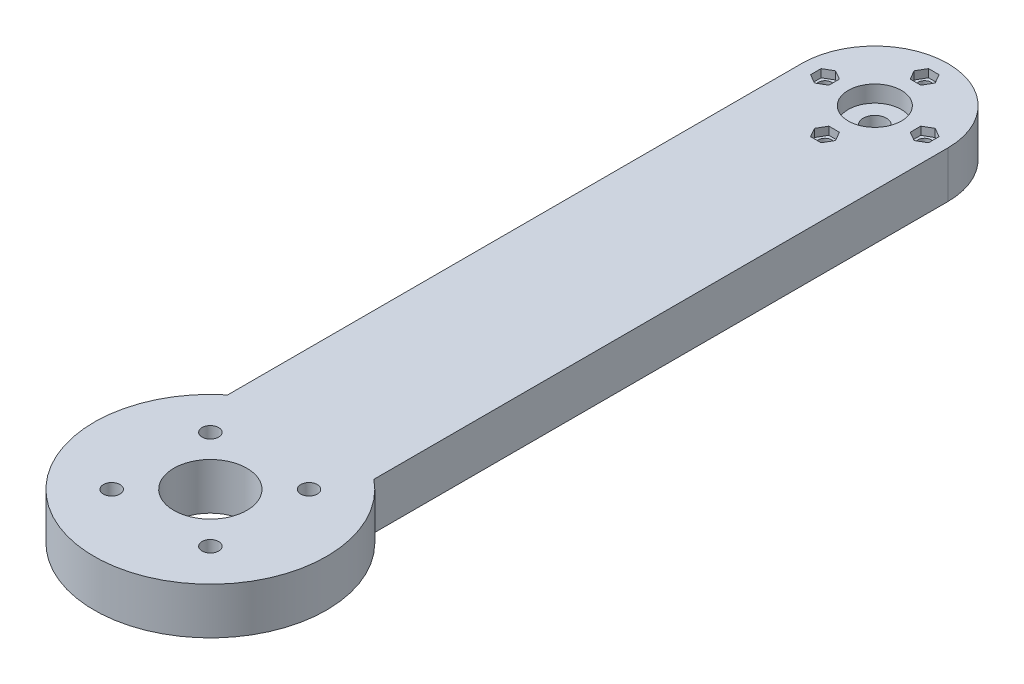
SolidWorks part; units mm, degrees
ref_plane "Front Plane" through (0, 0, 0) normal (0, 0, 1) x (1, 0, 0)
ref_plane "Top Plane" through (0, 0, 0) normal (0, 1, 0) x (1, 0, 0)
ref_plane "Right Plane" through (0, 0, 0) normal (1, 0, 0) x (0, 0, -1)
sketch "Sketch1" plane through (0, 0, 0) normal (0, 1, 0) x (1, 0, 0)
  line L0 (0, 0) -> (-42829.6201, 0) construction
  line L1 (0, 0) -> (0, -42829.6201) construction
  line L2 (-22, 0) -> (-22, -200)
  line L3 (22, 0) -> (22, -200)
  arc A0 (22, 0) -> (-22, 0) centre (0, 0) ccw
  arc A1 (-22, -200) -> (22, -200) centre (0, -200) ccw
  dimension "D1" = 44
  dimension "D2" = 44
  dimension "D3" = 200
extrude "Boss-Extrude1" add sketch "Sketch1" along normal blind 14
sketch "Sketch2" plane through (0, 14, 0) normal (0, 1, 0) x (1, 0, 0)
  line L0 (0, 0) -> (-50000, 0) construction
  line L1 (0, 0) -> (0, -50000) construction
  circle A0 centre (0, 0) radius 8
  dimension "D1" = 16
extrude "Cut-Extrude1" cut sketch "Sketch2" against normal blind 5
sketch "Sketch3" plane through (0, 14, 0) normal (0, 1, 0) x (1, 0, 0)
  line L0 (0, 0) -> (-50000, 0) construction
  line L1 (0, 0) -> (0, -50000) construction
  circle A0 centre (0, 0) radius 3.5
  dimension "D1" = 7
extrude "Cut-Extrude2" cut sketch "Sketch3" against normal through all
sketch "Sketch4" plane through (0, 14, 0) normal (0, 1, 0) x (1, 0, 0)
  line L0 (0, 0) -> (-50000, 0) construction
  line L1 (0, 0) -> (0, -50000) construction
  line L2 (15, -3.1754) -> (17.75, -1.5877)
  line L3 (3.1754, 15) -> (1.5877, 17.75)
  line L4 (1.5877, 17.75) -> (-1.5877, 17.75)
  line L5 (-1.5877, 17.75) -> (-3.1754, 15)
  line L6 (-3.1754, 15) -> (-1.5877, 12.25)
  line L7 (-1.5877, 12.25) -> (1.5877, 12.25)
  line L8 (1.5877, 12.25) -> (3.1754, 15)
  line L9 (17.75, -1.5877) -> (17.75, 1.5877)
  line L10 (17.75, 1.5877) -> (15, 3.1754)
  line L11 (15, 3.1754) -> (12.25, 1.5877)
  line L12 (12.25, 1.5877) -> (12.25, -1.5877)
  line L13 (12.25, -1.5877) -> (15, -3.1754)
  line L14 (-3.1754, -15) -> (-1.5877, -17.75)
  line L15 (-1.5877, -17.75) -> (1.5877, -17.75)
  line L16 (1.5877, -17.75) -> (3.1754, -15)
  line L17 (3.1754, -15) -> (1.5877, -12.25)
  line L18 (1.5877, -12.25) -> (-1.5877, -12.25)
  line L19 (-1.5877, -12.25) -> (-3.1754, -15)
  line L20 (-15, 3.1754) -> (-17.75, 1.5877)
  line L21 (-17.75, 1.5877) -> (-17.75, -1.5877)
  line L22 (-17.75, -1.5877) -> (-15, -3.1754)
  line L23 (-15, -3.1754) -> (-12.25, -1.5877)
  line L24 (-12.25, -1.5877) -> (-12.25, 1.5877)
  line L25 (-12.25, 1.5877) -> (-15, 3.1754)
  circle A1 centre (0, 0) radius 15 construction
  circle A6 centre (0, 15) radius 2.75 construction
  point P19 (0, 0)
  point P38 (0, 0)
  dimension "D1" = 30
  dimension "D2" = 5.5
  dimension "D3" = 4
extrude "Cut-Extrude9" cut sketch "Sketch4" against normal blind 2.4
sketch "Sketch7" plane through (0, 14, 0) normal (0, 1, 0) x (1, 0, 0)
  line L0 (0, 0) -> (-39424.2607, 0) construction
  line L1 (0, 0) -> (0, -50000) construction
  circle A2 centre (0, 0) radius 15 construction
  circle A3 centre (0, 15) radius 2
  circle A4 centre (15, 0) radius 2
  circle A5 centre (0, -15) radius 2
  circle A6 centre (-15, 0) radius 2
  point P19 (0, 0)
  dimension "D1" = 30
  dimension "D2" = 4
extrude "Cut-Extrude10" cut sketch "Sketch7" against normal through all
sketch "Sketch8" plane through (0, 0, 0) normal (0, 1, 0) x (1, 0, 0)
  line L0 (0, 0) -> (0, -50000) construction
  line L1 (0, 0) -> (-50000, 0) construction
  line L2 (0, -200) -> (-50000, -200) construction
  circle A0 centre (0, -200) radius 35
  dimension "D1" = 70
extrude "Boss-Extrude2" add sketch "Sketch8" along normal blind 14
sketch "Sketch9" plane through (0, 14, 0) normal (0, 1, 0) x (1, 0, 0)
  line L0 (0, 0) -> (0, -50000) construction
  line L1 (0, 0) -> (-50000, 0) construction
  line L2 (0, -200) -> (-50000, -200) construction
  line L3 (0, -200) -> (-35355.3391, 35155.3391) construction
  circle A4 centre (0, -200) radius 21 construction
  circle A5 centre (-14.8492, -185.1508) radius 2.5
  circle A6 centre (14.8492, -185.1508) radius 2.5
  circle A7 centre (14.8492, -214.8492) radius 2.5
  circle A8 centre (-14.8492, -214.8492) radius 2.5
  circle A9 centre (0, -200) radius 11
  point P24 (0, -200)
  dimension "D1" = 42
  dimension "D3" = 5
  dimension "D5" = 22
  dimension "D2" = 45
  dimension "D4" = 4
extrude "Cut-Extrude11" cut sketch "Sketch9" against normal through all
